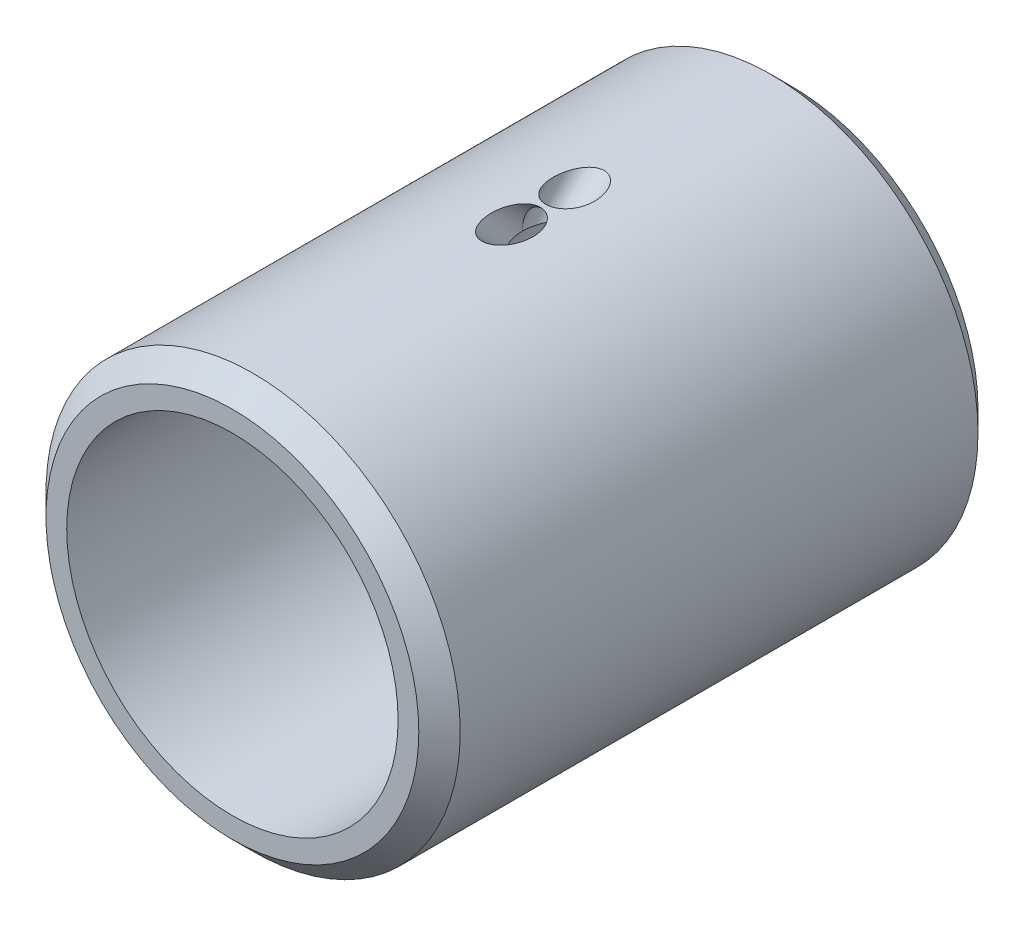
SolidWorks part; units mm, degrees
ref_plane "前视基准面" through (0, 0, 0) normal (0, 0, 1) x (1, 0, 0)
ref_plane "上视基准面" through (0, 0, 0) normal (0, 1, 0) x (1, 0, 0)
ref_plane "右视基准面" through (0, 0, 0) normal (1, 0, 0) x (0, 0, -1)
sketch "草图1" plane through (0, 0, 0) normal (0, 0, 1) x (1, 0, 0)
  circle A0 centre (0, 0) radius 10
  circle A1 centre (0, 0) radius 8
  dimension "D1" = 20
  dimension "D2" = 16
extrude "凸台-拉伸1" add sketch "草图1" along normal mid plane 27
chamfer "倒角1" distance 1 angle 45 2 edges at (10, 0, -13.5) (10, 0, 13.5)
sketch "草图2" plane through (0, 0, -13.5) normal (0, 0, -1) x (-1, 0, 0)
  circle A0 centre (0, 0) radius 8.5
  dimension "D1" = 17
extrude "切除-拉伸1" cut sketch "草图2" against normal blind 4 from offset 10 offset against normal yes
sketch "草图3" plane through (0, 0, 0) normal (1, 0, 0) x (0, 0, -1)
  line L0 (1.5, 3.6772) -> (1.5, 8.4586) construction
  line L1 (1.5, 8.4586) -> (5.9602, 12.9189)
  line L2 (1.5, 8.4586) -> (-2.9602, 12.9189)
  line L3 (13.5, -9) -> (13.5, 9) construction
  dimension "D1" = 12
  dimension "D2" = 90
sweep "切除-扫描1" cut path "草图3" circular profile diameter 2 parameters "D3"=2
